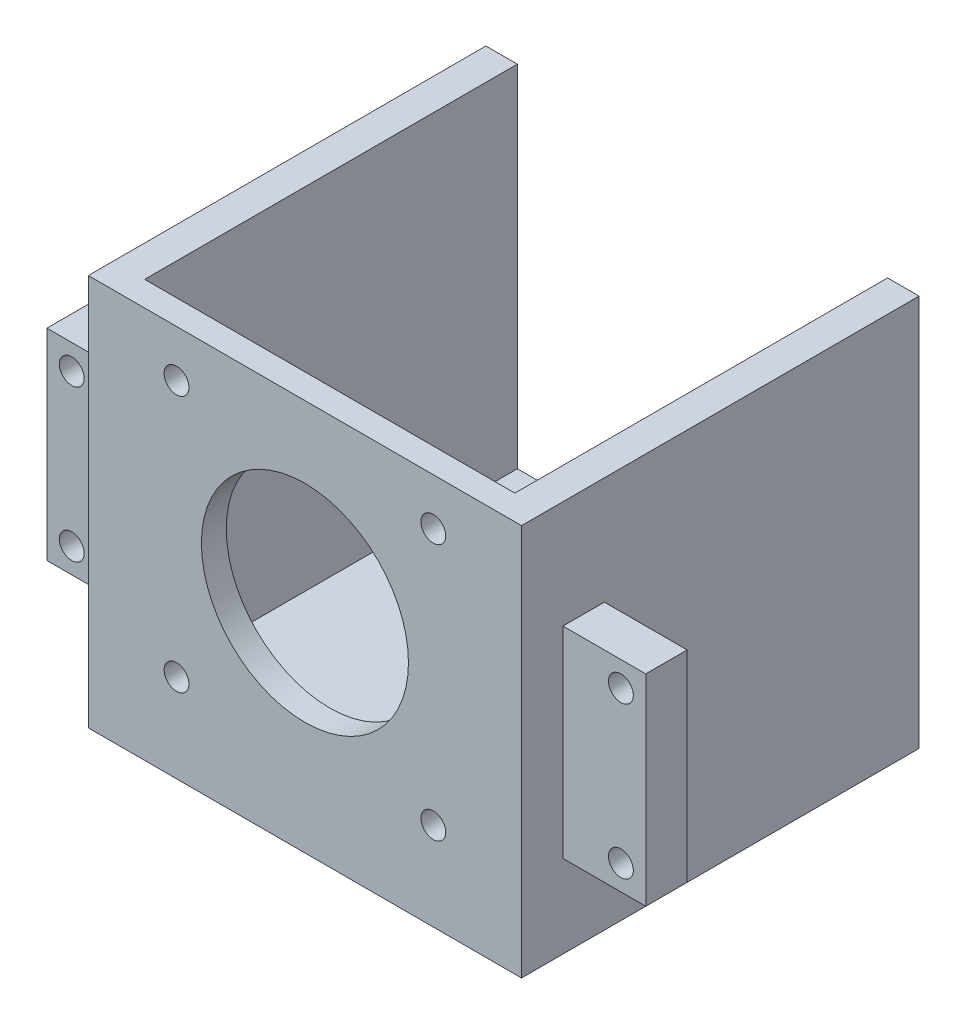
SolidWorks part; units mm, degrees
ref_plane "前视基准面" through (0, 0, 0) normal (0, 0, 1) x (1, 0, 0)
ref_plane "上视基准面" through (0, 0, 0) normal (0, 1, 0) x (1, 0, 0)
ref_plane "右视基准面" through (0, 0, 0) normal (1, 0, 0) x (0, 0, -1)
other "Configuration Table"
sketch "草图1" plane through (0, 0, 0) normal (0, 0, 1) x (1, 0, 0)
  line L1 (21.15, -21.15) -> (-21.15, -21.15)
  line L2 (21.15, -21.15) -> (21.15, 21.15)
  line L3 (21.15, 21.15) -> (-21.15, 21.15)
  line L4 (-21.15, -21.15) -> (-21.15, 21.15)
  line L5 (21.15, -21.15) -> (-21.15, 21.15) construction
  line L6 (21.15, 21.15) -> (-21.15, -21.15) construction
  point P0 (0, 0)
  dimension "D1" = 42.3
  dimension "D2" = 42.3
extrude "凸台-拉伸1" add sketch "草图1" along normal blind 3
sketch "草图2" plane through (0, 0, 3) normal (0, 0, 1) x (1, 0, 0)
  line L1 (15.5, -15.5) -> (-15.5, -15.5) construction
  line L2 (15.5, -15.5) -> (15.5, 15.5) construction
  line L3 (15.5, 15.5) -> (-15.5, 15.5) construction
  line L4 (-15.5, -15.5) -> (-15.5, 15.5) construction
  line L5 (15.5, -15.5) -> (-15.5, 15.5) construction
  line L6 (15.5, 15.5) -> (-15.5, -15.5) construction
  circle A0 centre (-15.5, 15.5) radius 1.5
  circle A1 centre (15.5, 15.5) radius 1.5
  circle A2 centre (15.5, -15.5) radius 1.5
  circle A3 centre (-15.5, -15.5) radius 1.5
  point P0 (0, 0)
  point P16 (0, 0)
  dimension "D3" = 4
  dimension "D1" = 31
  dimension "D2" = 31
extrude "切除-拉伸1" cut sketch "草图2" against normal blind 3
sketch "草图3" plane through (0, 0, 3) normal (0, 0, 1) x (1, 0, 0)
  circle A0 centre (0, 0) radius 12.5
  dimension "D1" = 25
extrude "切除-拉伸2" cut sketch "草图3" against normal blind 3
sketch "草图4" plane through (0, 0, 3) normal (0, 0, 1) x (1, 0, 0)
  line L0 (21.15, 21.15) -> (-21.15, 21.15) construction
  line L1 (26.15, -26.15) -> (-26.15, -26.15)
  line L2 (26.15, -26.15) -> (26.15, 26.15)
  line L3 (26.15, 26.15) -> (-26.15, 26.15)
  line L4 (-26.15, -26.15) -> (-26.15, 26.15)
  line L5 (26.15, -26.15) -> (-26.15, 26.15) construction
  line L6 (26.15, 26.15) -> (-26.15, -26.15) construction
  line L7 (-26.15, 21.15) -> (26.15, 21.15)
  line L8 (21.15, -21.15) -> (-21.15, -21.15)
  line L9 (21.15, -21.15) -> (21.15, 21.15)
  line L10 (21.15, 21.15) -> (-21.15, 21.15)
  line L11 (-21.15, -21.15) -> (-21.15, 21.15)
  line L12 (21.15, -21.15) -> (-21.15, 21.15) construction
  line L13 (21.15, 21.15) -> (-21.15, -21.15) construction
  point P0 (0, 0)
  point P8 (0, 0)
  line M14 (-21.15, 21.15) -> (-21.15, -21.15)
  line M15 (-21.15, -21.15) -> (21.15, -21.15)
  line M16 (21.15, -21.15) -> (21.15, 21.15)
  dimension "D1" = 5
extrude "凸台-拉伸2" add sketch "草图4" against normal blind 48 contours L7 L4 L1 L2 M16 M15 M14
sketch "草图5" plane through (-26.15, 0, 0) normal (-1, 0, 0) x (0, 0, 1)
  line L0 (-45, -26.15) -> (3, -26.15) construction
  line L1 (-7, -26.15) -> (-2, -26.15)
  line L2 (-7, -26.15) -> (-7, 21.15)
  line L3 (-7, 21.15) -> (-2, 21.15)
  line L4 (-2, -26.15) -> (-2, 21.15)
  line L5 (3, -26.15) -> (3, 21.15) construction
  line L6 (-45, 21.15) -> (3, 21.15) construction
  dimension "D1" = 5
  dimension "D2" = 5
extrude "凸台-拉伸3" add sketch "草图5" along normal blind 10
sketch "草图6" plane through (26.15, 0, 0) normal (1, 0, 0) x (0, 0, -1)
  line L0 (45, 21.15) -> (-3, 21.15) construction
  line L1 (2, -26.15) -> (7, -26.15)
  line L2 (2, -26.15) -> (2, 21.15)
  line L3 (2, 21.15) -> (7, 21.15)
  line L4 (7, -26.15) -> (7, 21.15)
  line L5 (-3, -26.15) -> (-3, 21.15) construction
  line L6 (45, -26.15) -> (-3, -26.15) construction
  dimension "D1" = 5
  dimension "D2" = 5
extrude "凸台-拉伸4" add sketch "草图6" along normal blind 10
sketch "草图7" plane through (0, 0, 3) normal (0, 0, 1) x (1, 0, 0)
  line L0 (0, -26.15) -> (0, 21.15) construction
  line L1 (26.15, -26.15) -> (-26.15, -26.15) construction
  line L2 (26.15, 21.15) -> (-26.15, 21.15) construction
  line L3 (-36.15, -26.15) -> (-36.15, 21.15) construction
  circle A0 centre (-33.15, -13.15) radius 1.5
  circle A1 centre (-33.15, 5.15) radius 1.5
  circle A2 centre (33.15, -13.15) radius 1.5
  circle A3 centre (33.15, 5.15) radius 1.5
  dimension "D1" = 16
  dimension "D2" = 3
  dimension "D3" = 13
extrude "切除-拉伸3" cut sketch "草图7" against normal blind 10
sketch "草图8" plane through (0, 21.15, 0) normal (0, 1, 0) x (1, 0, 0)
  line L0 (-22.35, 45) -> (-22.35, 0)
  line L1 (-26.15, 45) -> (-21.15, 45) construction
  line L2 (-22.35, 0) -> (22.35, 0)
  line L3 (22.35, 0) -> (22.35, 45)
  line L4 (21.15, 45) -> (26.15, 45) construction
  line L5 (22.35, 45) -> (-22.35, 45)
  line L6 (-21.15, 45) -> (-21.15, 0) construction
  line L7 (21.15, 45) -> (21.15, 0) construction
  dimension "D1" = 1.2
  dimension "D2" = 1.2
extrude "切除-拉伸4" cut sketch "草图8" against normal up to surface (42.3 mm away) up to face at (0, -21.15, -22.5)
sketch "草图10" plane through (0, 0, -2) normal (0, 0, 1) x (1, 0, 0)
  line L0 (-26.15, -26.15) -> (-26.15, 21.15) construction
  line L1 (-36.15, 21.15) -> (-26.15, 21.15)
  line L2 (-36.15, 21.15) -> (-36.15, 8.15)
  line L3 (-36.15, 8.15) -> (-26.15, 8.15)
  line L4 (-26.15, 21.15) -> (-26.15, 8.15)
  line L5 (26.15, 21.15) -> (26.15, -26.15) construction
  line L6 (36.15, 21.15) -> (26.15, 21.15)
  line L7 (36.15, 21.15) -> (36.15, 8.15)
  line L8 (36.15, 8.15) -> (26.15, 8.15)
  line L9 (26.15, 21.15) -> (26.15, 8.15)
  line L11 (-36.15, -26.15) -> (-26.15, -26.15)
  line L12 (-36.15, -26.15) -> (-36.15, -16.15)
  line L13 (-36.15, -16.15) -> (-26.15, -16.15)
  line L14 (-26.15, -26.15) -> (-26.15, -16.15)
  line L15 (36.15, -26.15) -> (26.15, -26.15)
  line L16 (36.15, -26.15) -> (36.15, -16.15)
  line L17 (36.15, -16.15) -> (26.15, -16.15)
  line L18 (26.15, -26.15) -> (26.15, -16.15)
  dimension "D1" = 13
  dimension "D2" = 13
  dimension "D3" = 10
  dimension "D4" = 10
extrude "切除-拉伸5" cut sketch "草图10" against normal blind 10
